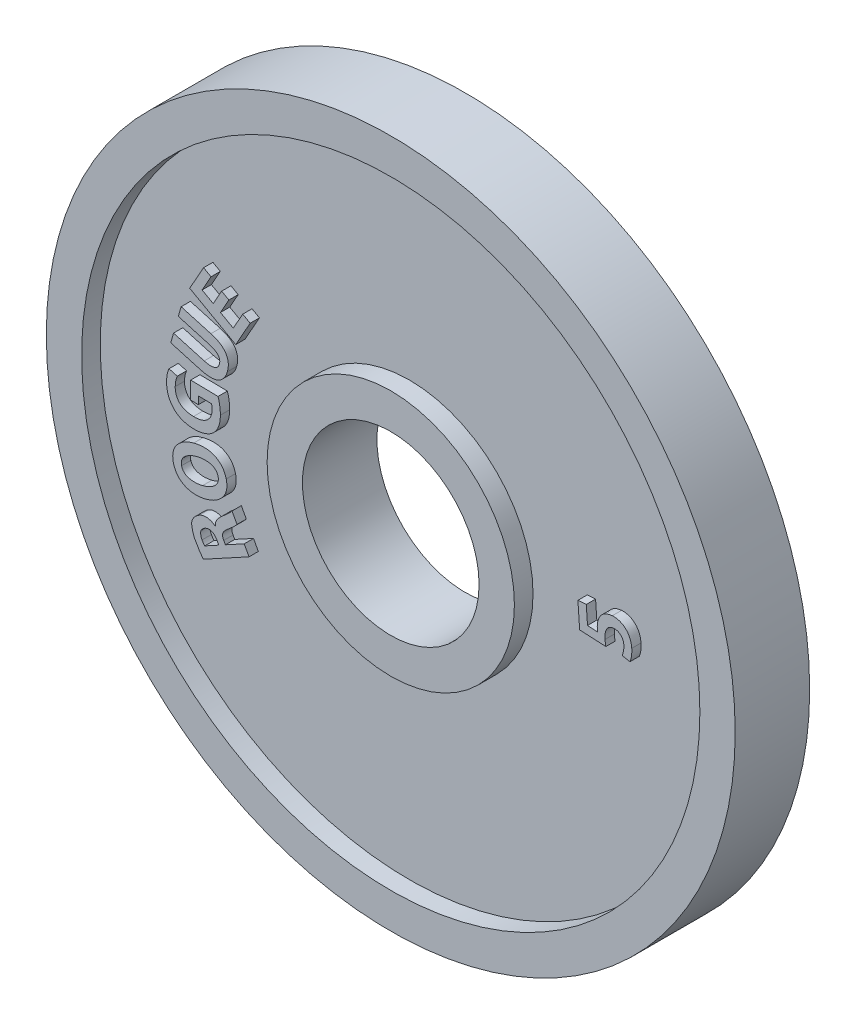
SolidWorks part; units mm, degrees
ref_plane "Front Plane" through (0, 0, 0) normal (0, 0, 1) x (1, 0, 0)
ref_plane "Top Plane" through (0, 0, 0) normal (0, 1, 0) x (1, 0, 0)
ref_plane "Right Plane" through (0, 0, 0) normal (1, 0, 0) x (0, 0, -1)
sketch "Sketch1" plane through (0, 0, 0) normal (0, 0, 1) x (1, 0, 0)
  circle A0 centre (0, 0) radius 97.5
  circle A1 centre (0, 0) radius 25
  dimension "D1" = 195
  dimension "D2" = 50
extrude "Boss-Extrude1" add sketch "Sketch1" along normal mid plane 21.082
sketch "Sketch3" plane through (0, 0, 10.541) normal (0, 0, 1) x (1, 0, 0)
  circle A0 centre (0, 0) radius 35
  circle A1 centre (0, 0) radius 87.5
  circle A2 centre (0, 0) radius 97.5 construction
  dimension "D1" = 10
  dimension "D2" = 35
extrude "Cut-Extrude1" cut sketch "Sketch3" against normal blind 5.2705
mirror "Mirror1" about plane through (0, 0, 0) normal (0, 0, 1) of "Cut-Extrude1"
sketch "Sketch4" plane through (0, 0, 5.2705) normal (0, 0, 1) x (1, 0, 0)
  text T0 "ROGUE" font "Adobe Gothic Std B" height in points 48
extrude "Boss-Extrude2" add sketch "Sketch4" along normal blind 2.6353
sketch "Sketch5" plane through (0, 0, 5.2705) normal (0, 0, 1) x (1, 0, 0)
  text T0 "5" font "Adobe Gothic Std B" height in points 48
extrude "Boss-Extrude3" add sketch "Sketch5" along normal blind 2.6353
